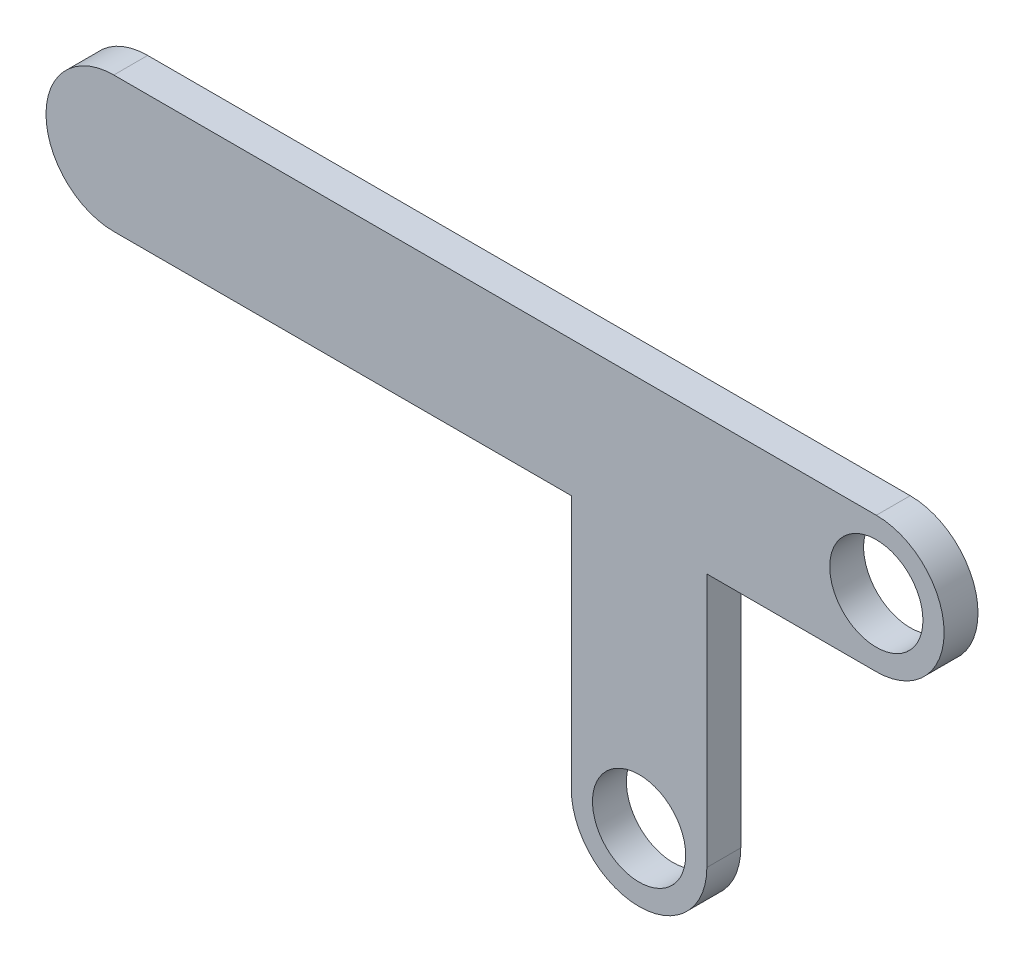
SolidWorks part; units mm, degrees
ref_plane "Front Plane" through (0, 0, 0) normal (0, 0, 1) x (1, 0, 0)
ref_plane "Top Plane" through (0, 0, 0) normal (0, 1, 0) x (1, 0, 0)
ref_plane "Right Plane" through (0, 0, 0) normal (1, 0, 0) x (0, 0, -1)
sketch "Sketch1" plane through (0, 0, 0) normal (0, 0, 1) x (1, 0, 0)
  line L0 (35, 0) -> (45, 0)
  line L1 (0, 0) -> (27, 0)
  line L3 (0, 8) -> (45, 8)
  line L6 (35, 0) -> (35, -15)
  line L8 (27, 0) -> (27, -15)
  arc A0 (0, 8) -> (0, 0) centre (0, 4) ccw
  arc A1 (45, 0) -> (45, 8) centre (45, 4) ccw
  arc A2 (27, -15) -> (35, -15) centre (31, -15) ccw
  circle A4 centre (45, 4) radius 2.75
  circle A5 centre (31, -15) radius 2.75
  dimension "D1" = 8
  dimension "D2" = 8
  dimension "D3" = 5.5
  dimension "D4" = 5.5
  dimension "D5" = 1.25
  dimension "D6" = 45
  dimension "D7" = 10
  dimension "D8" = 15
  dimension "D9" = 8
  dimension "D10" = 8
  dimension "D11" = 27
extrude "Boss-Extrude2" add sketch "Sketch1" along normal blind 2
